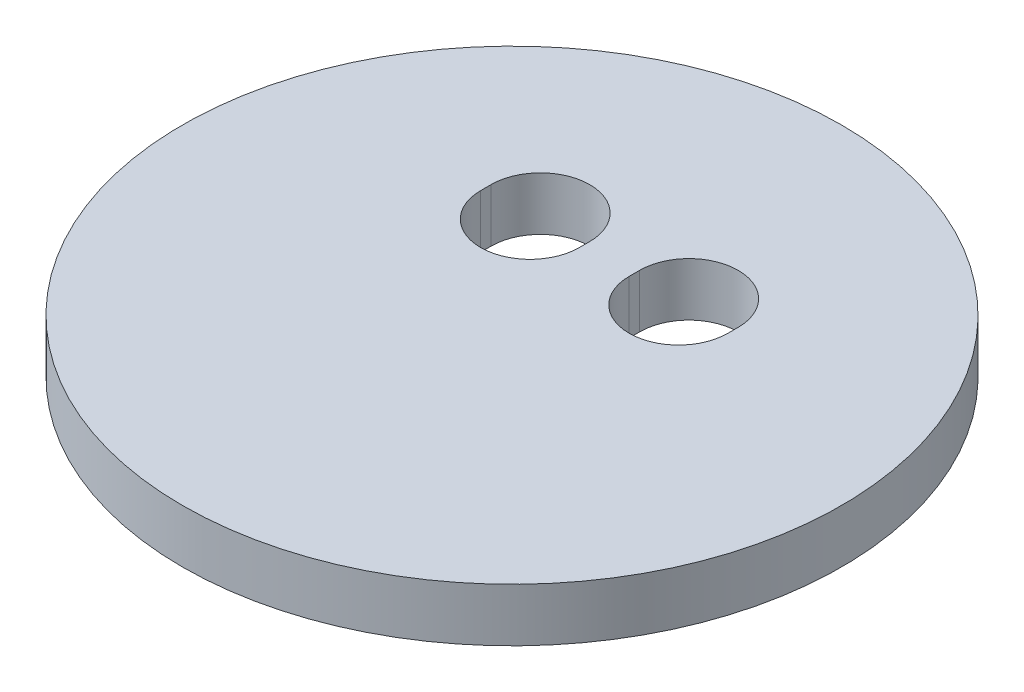
SolidWorks part; units mm, degrees
ref_plane "Front Plane" through (0, 0, 0) normal (0, 0, 1) x (1, 0, 0)
ref_plane "Top Plane" through (0, 0, 0) normal (0, 1, 0) x (1, 0, 0)
ref_plane "Right Plane" through (0, 0, 0) normal (1, 0, 0) x (0, 0, -1)
sketch "Sketch1" plane through (0, 0, 0) normal (0, 1, 0) x (1, 0, 0)
  circle A0 centre (0, 0) radius 12.36
  point P3 (0, 0)
  dimension "D1" = 24.72
extrude "Boss-Extrude1" add sketch "Sketch1" along normal blind 2
sketch "Sketch2" plane through (0, 2, 0) normal (0, 1, 0) x (1, 0, 0)
  line L0 (-2.785, 3.85) -> (-2.785, 3.46) construction
  line L1 (2.785, 3.85) -> (2.785, 3.46) construction
  line L2 (4.635, 3.85) -> (4.635, 3.46)
  line L3 (0.935, 3.85) -> (0.935, 3.46)
  line L4 (-0.935, 3.85) -> (-0.935, 3.46)
  line L5 (-4.635, 3.85) -> (-4.635, 3.46)
  line L6 (-2.785, 5.7) -> (2.785, 5.7) construction
  arc A3 (4.635, 3.85) -> (0.935, 3.85) centre (2.785, 3.85) ccw
  arc A4 (0.935, 3.46) -> (4.635, 3.46) centre (2.785, 3.46) ccw
  arc A5 (-0.935, 3.85) -> (-4.635, 3.85) centre (-2.785, 3.85) ccw
  arc A6 (-4.635, 3.46) -> (-0.935, 3.46) centre (-2.785, 3.46) ccw
  circle A7 centre (0, 0) radius 12.36 construction
  point P1 (-2.785, 3.655)
  point P2 (-4.635, 3.655)
  point P3 (-0.935, 3.655)
  point P8 (2.785, 3.655)
  point P14 (2.785, 5.7)
  point P15 (2.785, 1.61)
  point P16 (4.635, 3.655)
  point P17 (0.935, 3.655)
  point P20 (-2.785, 5.7)
  point P24 (-2.785, 1.61)
  point P29 (0, 5.7)
  dimension "D2" = 4.09
  dimension "D1" = 3.7
  dimension "D3" = 3.7
  dimension "D4" = 4.09
  dimension "D5" = 5.7
  dimension "D6" = 5.57
extrude "Cut-Extrude1" cut sketch "Sketch2" against normal through all
